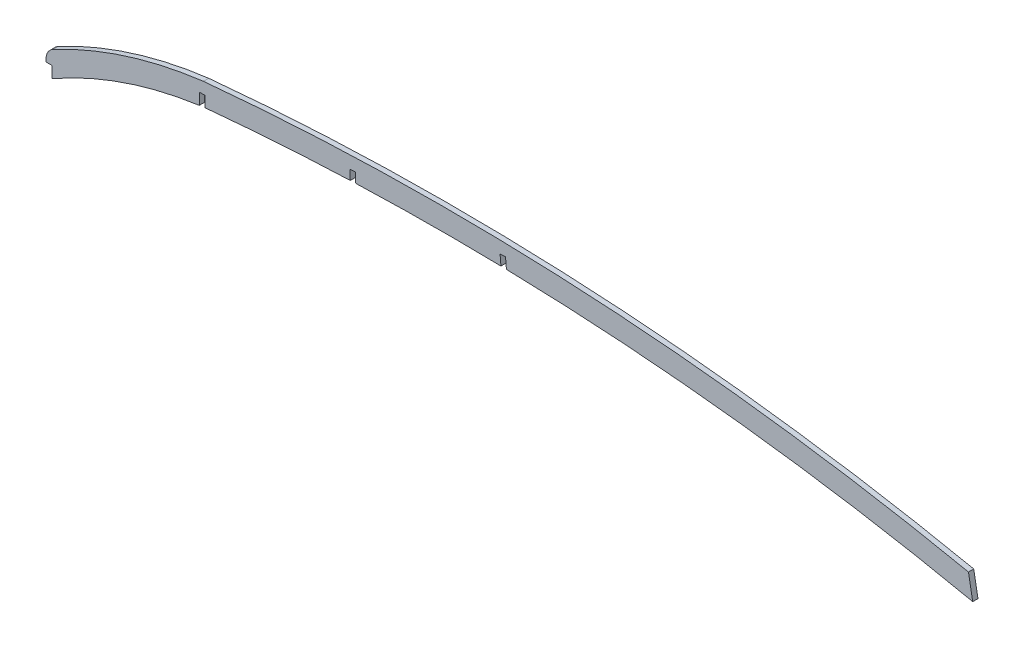
SolidWorks part; units mm, degrees
material "Balsa"
ref_plane "Front Plane" through (0, 0, 0) normal (0, 0, 1) x (1, 0, 0)
ref_plane "Top Plane" through (0, 0, 0) normal (0, 1, 0) x (1, 0, 0)
ref_plane "Right Plane" through (0, 0, 0) normal (1, 0, 0) x (0, 0, -1)
sketch "Sketch1" plane through (0, 0, 0) normal (0, 0, 1) x (1, 0, 0)
  line L0 (0, 101.6) -> (0, 100.0553)
  line L1 (0, -1.7463) -> (0, 1.7463) construction
  line L2 (0, 86.36) -> (8.1082, 86.36) construction
  line L3 (3.7499, 106.3536) -> (3.7499, -82.5359) construction
  line L4 (8.1082, 101.6) -> (0, 101.6) construction
  line L5 (92.329, 130.518) -> (92.329, 123.5672)
  line L6 (3.7499, 93.1973) -> (0, 91.0322) construction
  line L7 (0, 99.5163) -> (0, 88.039) construction
  line L8 (558.2295, 97.6273) -> (555.6382, 111.8229)
  line L9 (0, 91.0322) -> (0, 86.36) construction
  line L10 (3.7499, 93.1973) -> (3.7499, 100.0553)
  line L11 (3.7499, 100.0553) -> (0, 97.8902) construction
  line L12 (0, 97.8902) -> (0, 91.0322) construction
  line L13 (3.7499, 100.0553) -> (0, 100.0553)
  line L14 (0, 100.0553) -> (0, 97.8902) construction
  line L17 (92.3925, 137.6297) -> (92.3925, -54.5591) construction
  line L18 (95.631, 130.518) -> (95.631, 124.0109)
  line L19 (95.5675, -54.5591) -> (95.5675, 137.6297) construction
  line L20 (95.5675, 137.6297) -> (92.3925, 137.6297) construction
  line L21 (93.98, 137.6297) -> (93.98, 130.518) construction
  line L22 (92.329, 130.518) -> (95.631, 130.518)
  line L23 (92.329, 123.5672) -> (92.329, 122.506) construction
  line L24 (95.631, 124.0109) -> (95.631, 123.1918) construction
  line L25 (197.4984, -131.9724) -> (196.7865, -114.9693)
  line L26 (186.671, 126.627) -> (186.2782, 136.0069)
  line L27 (194.3262, -132.1052) -> (193.6143, -115.1021)
  line L28 (183.4987, 126.4942) -> (183.106, 135.8741)
  line L29 (193.6143, -115.1021) -> (196.7865, -114.9693)
  line L30 (186.671, 126.627) -> (183.4987, 126.4942)
  line L31 (194.3262, -132.1052) -> (197.4984, -131.9724)
  line L32 (183.106, 135.8741) -> (186.2782, 136.0069)
  line L33 (183.106, 135.8741) -> (186.2782, 136.0069) construction
  line L35 (186.671, 126.627) -> (183.4987, 126.4942) construction
  line L37 (183.4987, 126.4942) -> (183.106, 135.8741) construction
  line L39 (186.671, 126.627) -> (186.2782, 136.0069) construction
  line L41 (183.106, 135.8741) -> (186.671, 126.627) construction
  line L42 (184.8885, 131.2506) -> (184.9758, 129.1656) construction
  line L43 (183.294, 129.865) -> (183.0502, 135.6897)
  line L44 (186.5939, 129.9858) -> (186.3493, 135.8278)
  line L45 (183.0502, 135.6897) -> (186.3493, 135.8278)
  line L46 (183.2948, 129.8477) -> (183.294, 129.865) construction
  line L47 (276.7538, 136.7291) -> (273.5905, 136.4568)
  line L48 (298.3406, -114.0477) -> (295.1773, -114.32)
  line L49 (274.4392, 126.5971) -> (277.6025, 126.8694)
  line L50 (273.5905, 136.4568) -> (274.4392, 126.5971)
  line L51 (295.1773, -114.32) -> (296.6804, -131.7814)
  line L52 (276.7538, 136.7291) -> (277.6025, 126.8694)
  line L53 (298.3406, -114.0477) -> (299.8437, -131.5091)
  line L54 (296.6804, -131.7814) -> (299.8437, -131.5091)
  line L57 (276.7538, 136.7291) -> (277.6025, 126.8694) construction
  line L59 (273.5905, 136.4568) -> (274.4392, 126.5971) construction
  line L60 (274.4392, 126.5971) -> (277.6025, 126.8694) construction
  line L63 (274.4392, 126.5971) -> (276.7538, 136.7291) construction
  line L64 (275.5965, 131.6631) -> (274.3291, 146.3866) construction
  line L65 (274.0318, 130.5899) -> (273.5181, 136.5576)
  line L66 (277.3525, 130.5142) -> (276.8079, 136.8408)
  line L67 (273.5181, 136.5576) -> (276.8079, 136.8408)
  line L68 (274.0627, 130.231) -> (274.0318, 130.5899) construction
  line L69 (276.7538, 136.7291) -> (273.5905, 136.4568)
  arc A0 (4.3005, 108.7585) -> (94.8544, 137.376) centre (127, -121.92) cw
  arc A1 (4.3005, 108.7585) -> (0, 101.6) centre (8.1082, 101.6) ccw
  arc A2 (3.7499, 93.1973) -> (0, 86.36) centre (8.1082, 86.36) ccw construction
  arc A3 (94.8544, 137.376) -> (555.6382, 111.8229) centre (240.8652, -1397) cw
  arc A4 (3.7499, 93.1973) -> (92.329, 123.5672) centre (127, -121.92) cw
  arc A5 (96.3112, 124.0967) -> (183.294, 129.865) centre (240.8652, -1397) cw
  arc A6 (10.5733, 96.9655) -> (96.3112, 124.0967) centre (127, -121.92) cw construction
  arc A7 (94.4927, 137.3434) -> (3.7499, 106.3536) centre (112.883, -64.8553) ccw construction
  arc A8 (96.3112, 124.0967) -> (552.9103, 98.7469) centre (240.8652, -1397) cw construction
  arc A9 (4.3005, 108.7585) -> (94.8544, 137.376) centre (127, -121.92) cw construction
  arc A10 (92.329, 123.5672) -> (95.631, 124.0109) centre (127, -121.92) cw construction
  arc A11 (94.8544, 137.376) -> (555.6382, 111.8229) centre (240.8652, -1397) cw construction
  arc A12 (95.631, 124.0109) -> (96.3112, 124.0967) centre (127, -121.92) cw
  arc A13 (556.7512, 105.7321) -> (99.1899, 122.2822) centre (270.5046, -1474.7614) ccw construction
  arc A14 (183.294, 129.865) -> (183.3575, 129.8673) centre (240.8652, -1397) cw construction
  arc A15 (184.9439, 129.9263) -> (185.3927, 129.9426) centre (240.8652, -1397) cw construction
  arc A16 (183.3575, 129.8673) -> (184.9439, 129.9263) centre (240.8652, -1397) cw construction
  arc A17 (185.3927, 129.9426) -> (186.5304, 129.9835) centre (240.8652, -1397) cw construction
  arc A18 (186.5939, 129.9858) -> (274.0318, 130.5899) centre (240.8652, -1397) cw
  arc A19 (186.5304, 129.9835) -> (186.5939, 129.9858) centre (240.8652, -1397) cw construction
  arc A20 (274.0957, 130.5885) -> (275.3447, 130.5609) centre (240.8652, -1397) cw construction
  arc A21 (277.3525, 130.5142) -> (558.2295, 97.6273) centre (240.8652, -1397) cw
  arc A22 (274.0318, 130.5899) -> (274.0957, 130.5885) centre (240.8652, -1397) cw construction
  arc A23 (275.3447, 130.5609) -> (277.2887, 130.5157) centre (240.8652, -1397) cw construction
  arc A24 (277.2887, 130.5157) -> (277.3525, 130.5142) centre (240.8652, -1397) cw construction
  spline S0 degree 3 poles (981.3177, 1818.2675) (1139.722, 204.4849) (873.2182, 1.0169) (565.628, -88.9106) (559.2919, -90.7077) (-121.8164, -278.7114) (-929.5333, 36.0269) (-1233.6865, -867.5095) knots -11.664502 -11.664502 -11.664502 -11.664502 0.25 0.25 0.5 0.5 27.071012 27.071012 27.071012 27.071012 only from (590.8643, -81.3536) to (514.7143, -102.4537) construction
  spline S1 degree 3 poles (1062.5522, -1662.3274) (1783.386, 752.2598) (1192.007, 51.9761) (480.6823, -110.4688) (472.1454, -112.3347) (455.0337, -115.879) (446.4591, -117.5582) (433.5613, -119.8984) (429.2558, -120.648) (422.7903, -121.7356) (420.6337, -122.0915) (417.3979, -122.6188) (416.3191, -122.7935) (329.7173, -136.7537) (244.3749, -151.8452) (-150.7518, 1789.6158) knots -20.37019 -20.37019 -20.37019 -20.37019 0.25 0.25 0.5 0.5 0.75 0.75 0.875 0.875 0.9375 0.9375 0.96875 0.96875 3.445896 3.445896 3.445896 3.445896 only from (514.7143, -102.4537) to (412.003, -123.4859) construction
  spline S2 degree 3 poles (-1526.2092, 975.8893) (-966.7298, 244.4948) (-373.5074, -121.9571) (226.7788, -133.168) (266.5142, -132.8729) (279.7628, -132.6016) (299.6408, -131.9345) (306.2677, -131.6688) (319.5231, -131.0505) (326.1536, -130.6977) (943.6584, -93.7895) (1501.3881, 309.0053) (2017.121, 1001.2295) knots -5.168103 -5.168103 -5.168103 -5.168103 0.25 0.5 0.5 0.625 0.625 0.6875 0.6875 0.75 0.75 6.511417 6.511417 6.511417 6.511417 only from (94.4926, -125.8525) to (412.003, -123.4859) construction
  spline S3 degree 3 poles (82.8406, 1879.826) (-241.5287, 509.6599) (-195.4311, -0.6421) (32.0968, -110.0953) (39.5136, -113.1375) (50.922, -117.0433) (54.7721, -118.2354) (60.6197, -119.8556) (62.5829, -120.3681) (66.5243, -121.3341) (68.5001, -121.787) (343.1899, -180.4478) (711.1357, 326.3263) (1193.75, 1513.3939) knots -7.368418 -7.368418 -7.368418 -7.368418 0.25 0.25 0.5 0.5 0.625 0.625 0.6875 0.6875 0.75 0.75 9.354609 9.354609 9.354609 9.354609 only from (3.7499, -94.8626) to (94.4926, -125.8525) construction
  spline S6 degree 3 poles (590.8643, -81.3536) (584.5771, -83.3154) (578.2709, -85.2143) (565.628, -88.9106) (559.2919, -90.7077) (540.2459, -95.9648) (527.5015, -99.2922) (514.7143, -102.4537) knots 0 0 0 0 0.25 0.25 0.5 0.5 1 1 1 1 construction
  spline S7 degree 3 poles (514.7143, -102.4537) (506.2284, -104.5517) (497.724, -106.577) (480.6823, -110.4688) (472.1454, -112.3347) (455.0337, -115.879) (446.4591, -117.5582) (433.5613, -119.8984) (429.2558, -120.648) (422.7903, -121.7356) (420.6337, -122.0915) (417.3979, -122.6188) (416.3191, -122.7935) (414.1613, -123.1413) (413.0825, -123.3155) (412.003, -123.4859) knots 0 0 0 0 0.25 0.25 0.5 0.5 0.75 0.75 0.875 0.875 0.9375 0.9375 0.96875 0.96875 1 1 1 1 construction
  spline S8 degree 3 poles (94.4926, -125.8525) (120.9278, -128.4258) (173.8258, -132.179) (226.7788, -133.168) (266.5142, -132.8729) (279.7628, -132.6016) (299.6408, -131.9345) (306.2677, -131.6688) (319.5231, -131.0505) (326.1536, -130.6977) (359.2877, -128.7173) (385.6949, -126.4433) (412.003, -123.4859) knots 0 0 0 0 0.25 0.5 0.5 0.625 0.625 0.6875 0.6875 0.75 0.75 1 1 1 1 construction
  spline S9 degree 3 poles (3.7499, -94.8626) (10.597, -99.2271) (17.6385, -103.1401) (32.0968, -110.0953) (39.5136, -113.1375) (50.922, -117.0433) (54.7721, -118.2354) (60.6197, -119.8556) (62.5829, -120.3681) (66.5243, -121.3341) (68.5001, -121.787) (78.4043, -123.9021) (86.408, -125.1172) (94.4926, -125.8525) knots 0 0 0 0 0.25 0.25 0.5 0.5 0.625 0.625 0.6875 0.6875 0.75 0.75 1 1 1 1 construction
  spline S15 degree 3 poles (587.4426, -62.5747) (587.1827, -61.1511) (586.6535, -58.2526) (585.7873, -53.5174) (584.8512, -48.394) (583.8406, -42.8532) (582.7565, -36.9006) (581.5991, -30.5376) (580.1295, -22.4773) (578.3524, -12.6853) (576.2505, -1.1976) (574.1192, 10.4518) (571.9272, 22.5233) (569.819, 34.0829) (567.7342, 45.5019) (565.8232, 55.9911) (564.3841, 63.8754) (563.4512, 68.9947) (562.9209, 71.9076) (562.4102, 74.7138) (561.9192, 77.4122) (561.4478, 80.0018) (560.9959, 82.4822) (560.5637, 84.8528) (560.1512, 87.1138) (559.7582, 89.2651) (559.385, 91.3073) (559.0312, 93.2414) (558.6975, 95.0661) (558.3822, 96.7905) (558.1867, 97.8615) (558.0896, 98.3936) knots 0 0 0 0 0.031687 0.064515 0.098497 0.133644 0.169967 0.207478 0.246191 0.30842 0.370332 0.432609 0.495165 0.563925 0.620591 0.686243 0.746551 0.766006 0.785258 0.804303 0.823142 0.841774 0.860197 0.878411 0.896416 0.91421 0.931793 0.949164 0.966322 0.983268 1 1 1 1 construction
  point P53 (93.98, 130.518)
  dimension "D4" = 8.1082
  dimension "D2" = 127
  dimension "D8" = 1397
  dimension "D9" = 30
  dimension "D1" = 15.24
  dimension "D3" = 8.1082
  dimension "D5" = 8.1082
  dimension "D6" = 101.6
  dimension "D7" = 121.92
  dimension "D10" = 6.858
  dimension "D11" = 3.7499
  dimension "D12" = 3.302
  dimension "D13" = 6.858
  dimension "D14" = 3.302
  dimension "D15" = 5.842
  dimension "D16" = 3.302
  dimension "D17" = 6.35
extrude "Boss-Extrude1" add sketch "Sketch1" along normal mid plane 3.175 contours L66 A21 L8 A3 A0 A1 L0 L13 L10 A4 L5 L22 L18 A12 A5 L43 L45 L44 A18 L65 L67
equation "\"slotwidth\"=0.167708"
